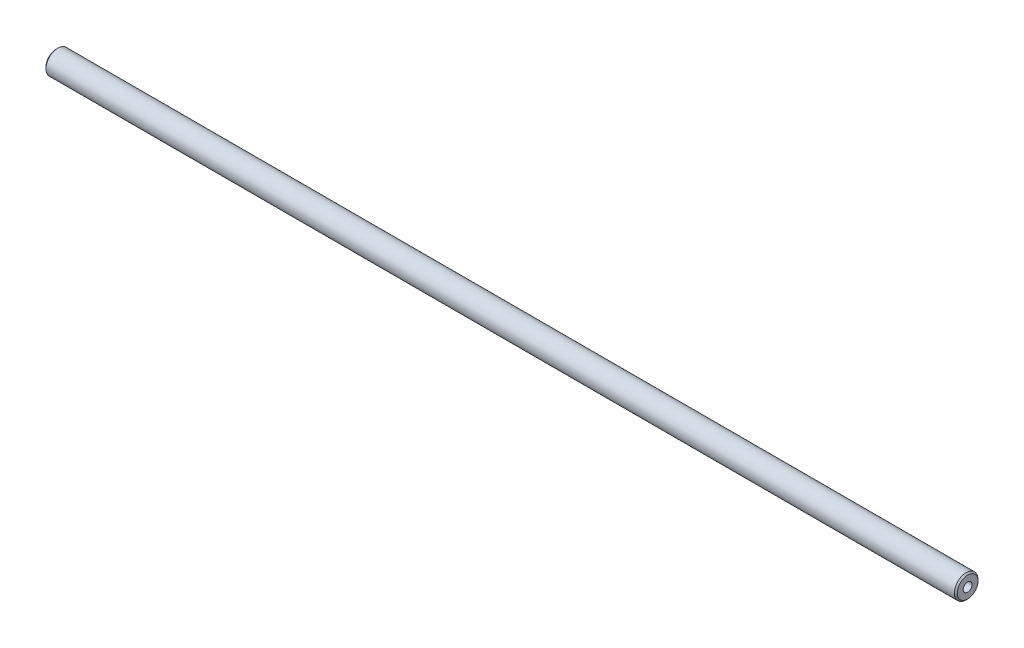
SolidWorks part; units mm, degrees
ref_plane "Спереди" through (0, 0, 0) normal (0, 0, 1) x (1, 0, 0)
ref_plane "Сверху" through (0, 0, 0) normal (0, 1, 0) x (1, 0, 0)
ref_plane "Справа" through (0, 0, 0) normal (1, 0, 0) x (0, 0, -1)
sketch "Эскиз1" plane through (0, 0, 0) normal (0, 0, 1) x (1, 0, 0)
  line L0 (-146, 1.5) -> (-146, 0)
  line L1 (-146, 0) -> (146, 0)
  line L2 (146, 0) -> (146, 1.5)
  line L3 (146, 1.5) -> (154, 1.5)
  line L4 (154, 1.5) -> (154, 3.5)
  line L5 (154, 3.5) -> (153.5, 4)
  line L6 (153.5, 4) -> (-153.5, 4)
  line L7 (-153.5, 4) -> (-154, 3.5)
  line L8 (-154, 3.5) -> (-154, 1.5)
  line L9 (-154, 1.5) -> (-146, 1.5)
  line L10 (-154, 0) -> (154, 0) construction
revolve "Повернуть1" add sketch "Эскиз1" angle 360 about L10
